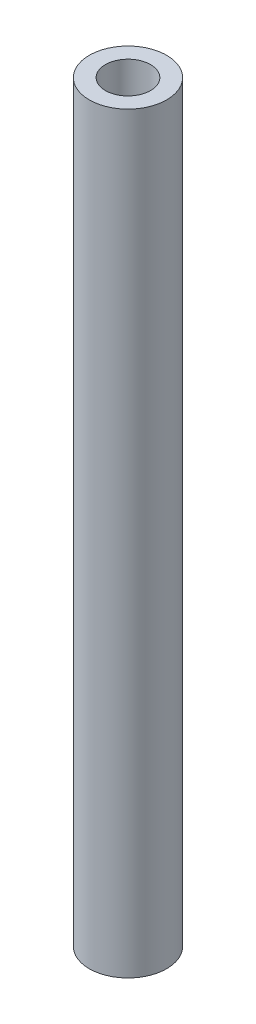
SolidWorks part; units mm, degrees
ref_plane "Front Plane" through (0, 0, 0) normal (0, 0, 1) x (1, 0, 0)
ref_plane "Top Plane" through (0, 0, 0) normal (0, 1, 0) x (1, 0, 0)
ref_plane "Right Plane" through (0, 0, 0) normal (1, 0, 0) x (0, 0, -1)
sketch "Sketch2" plane through (0, 0, 0) normal (0, 1, 0) x (1, 0, 0)
  circle A0 centre (0, 0) radius 6.096
  circle A1 centre (0, 0) radius 3.556
extrude "Boss-Extrude1" add sketch "Sketch2" along normal blind 118.618
